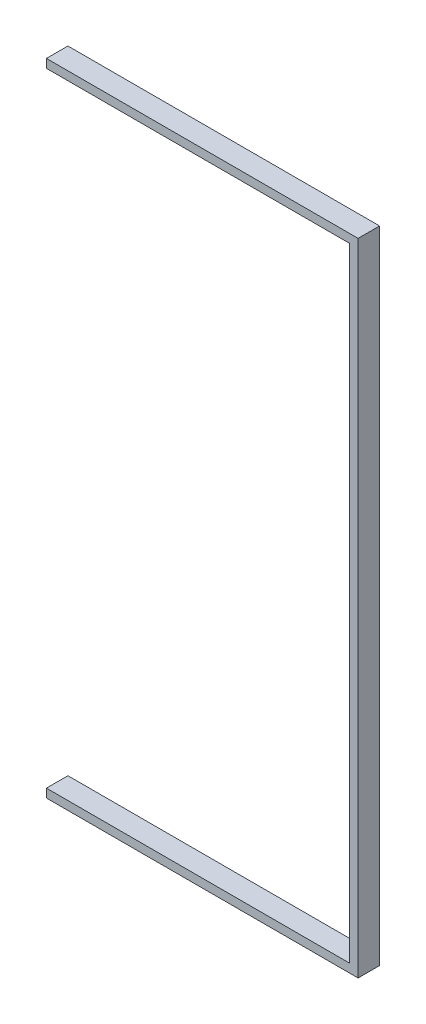
SolidWorks part; units mm, degrees
ref_plane "Спереди" through (0, 0, 0) normal (0, 0, 1) x (1, 0, 0)
ref_plane "Сверху" through (0, 0, 0) normal (0, 1, 0) x (1, 0, 0)
ref_plane "Справа" through (0, 0, 0) normal (1, 0, 0) x (0, 0, -1)
sketch "Эскиз1" plane through (0, 0, 0) normal (0, 0, 1) x (1, 0, 0)
  line L0 (-141, 41.0198) -> (0, 41.0198)
  line L1 (0, 41.0198) -> (0, -248.9802)
  line L2 (0, -248.9802) -> (-141, -248.9802)
  line L3 (-141, -248.9802) -> (-141, -252.9802)
  line L4 (-141, -252.9802) -> (4, -252.9802)
  line L5 (4, -252.9802) -> (4, 45.0198)
  line L6 (4, 45.0198) -> (-141, 45.0198)
  line L7 (-141, 45.0198) -> (-141, 41.0198)
  dimension "D1" = 4
  dimension "D2" = 4
  dimension "D3" = 290
  dimension "D4" = 145
extrude "Бобышка-Вытянуть1" add sketch "Эскиз1" along normal blind 10
